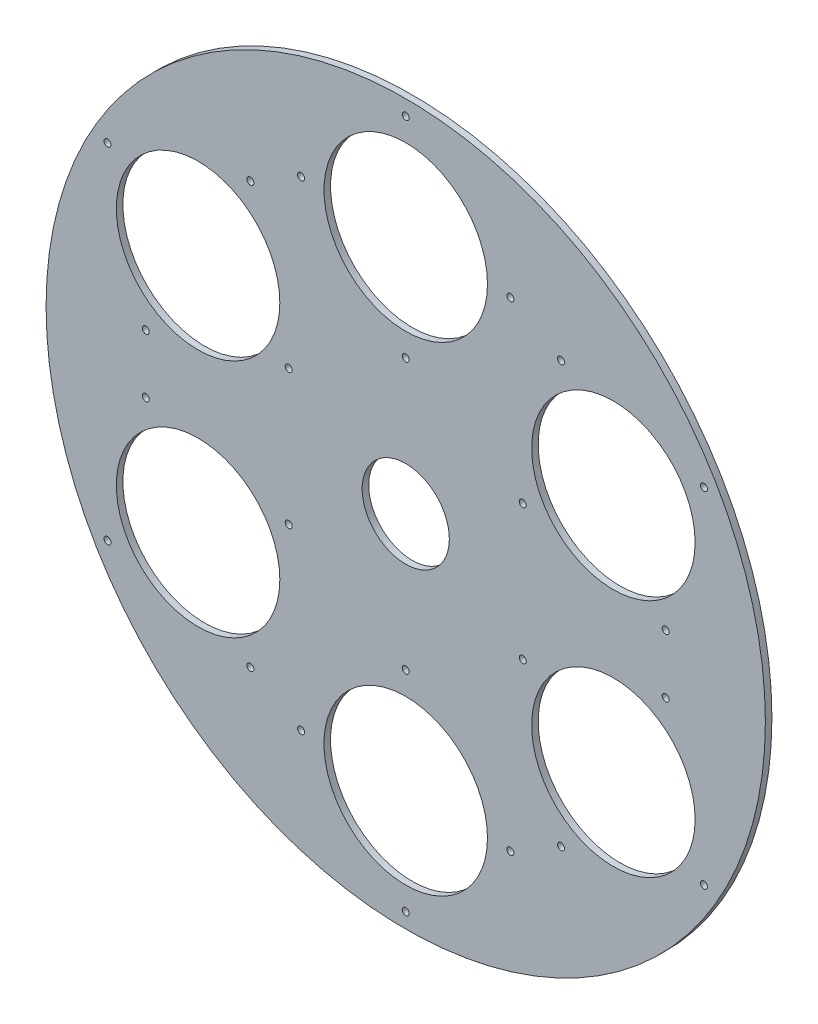
SolidWorks part; units mm, degrees
ref_plane "Front Plane" through (0, 0, 0) normal (0, 0, 1) x (1, 0, 0)
ref_plane "Top Plane" through (0, 0, 0) normal (0, 1, 0) x (1, 0, 0)
ref_plane "Right Plane" through (0, 0, 0) normal (1, 0, 0) x (0, 0, -1)
sketch "Sketch11" plane through (0, 0, 0) normal (0, 0, 1) x (1, 0, 0)
  circle A7 centre (0, 0) radius 165
  circle A9 centre (-48, 110) radius 1.6
  circle A11 centre (0, 158) radius 1.6
  circle A12 centre (48, 110) radius 1.6
  circle A13 centre (0, 62) radius 1.6
  circle A14 centre (71.2628, 96.5692) radius 1.6
  circle A15 centre (136.832, 79) radius 1.6
  circle A16 centre (119.2628, 13.4308) radius 1.6
  circle A17 centre (53.6936, 31) radius 1.6
  circle A18 centre (119.2628, -13.4308) radius 1.6
  circle A19 centre (136.832, -79) radius 1.6
  circle A20 centre (71.2628, -96.5692) radius 1.6
  circle A21 centre (53.6936, -31) radius 1.6
  circle A22 centre (48, -110) radius 1.6
  circle A23 centre (0, -158) radius 1.6
  circle A24 centre (-48, -110) radius 1.6
  circle A25 centre (0, -62) radius 1.6
  circle A26 centre (-71.2628, -96.5692) radius 1.6
  circle A27 centre (-136.832, -79) radius 1.6
  circle A28 centre (-119.2628, -13.4308) radius 1.6
  circle A29 centre (-53.6936, -31) radius 1.6
  circle A30 centre (-119.2628, 13.4308) radius 1.6
  circle A31 centre (-136.832, 79) radius 1.6
  circle A32 centre (-71.2628, 96.5692) radius 1.6
  circle A33 centre (-53.6936, 31) radius 1.6
  circle A34 centre (0, 110) radius 37.5
  circle A35 centre (95.2628, 55) radius 37.5
  circle A36 centre (95.2628, -55) radius 37.5
  circle A37 centre (0, -110) radius 37.5
  circle A38 centre (-95.2628, -55) radius 37.5
  circle A39 centre (-95.2628, 55) radius 37.5
  circle A40 centre (0, 0) radius 20
  point P14 (95.2628, 55)
  point P17 (0, 0)
  point P27 (0, 110)
  point P32 (95.2628, -55)
  point P41 (0, -110)
  point P50 (-95.2628, -55)
  point P59 (-95.2628, 55)
  point P60 (0, 0)
  point P62 (0, 0)
  point P73 (0, 0)
  dimension "D1" = 6
  dimension "D2" = 6
extrude "Boss-Extrude4" add sketch "Sketch11" along normal blind 3
